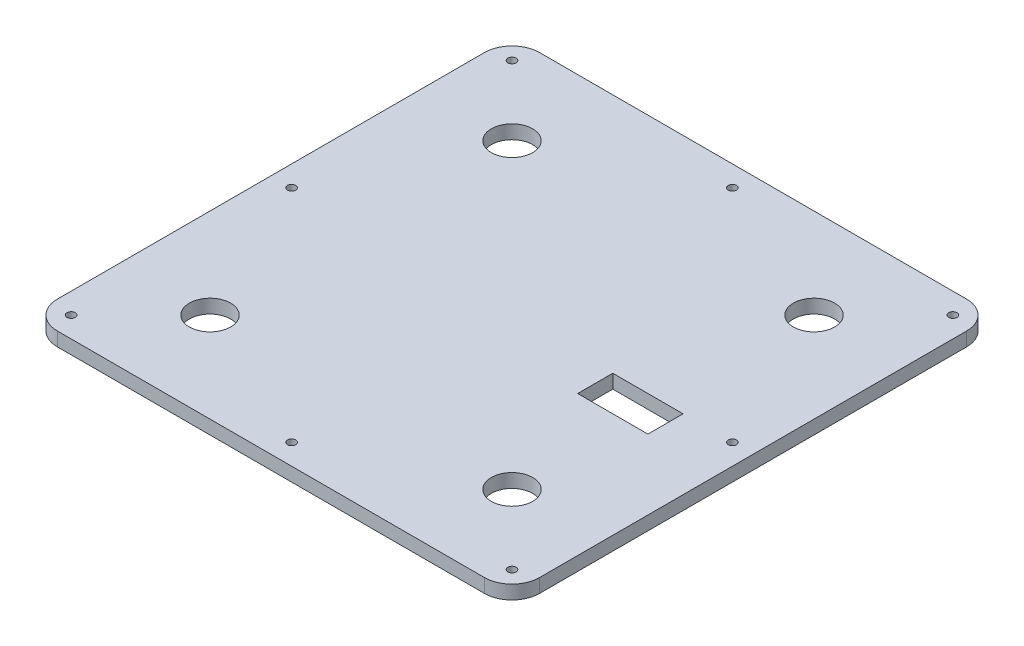
SolidWorks part; units mm, degrees
ref_plane "Front Plane" through (0, 0, 0) normal (0, 0, 1) x (1, 0, 0)
ref_plane "Top Plane" through (0, 0, 0) normal (0, 1, 0) x (1, 0, 0)
ref_plane "Right Plane" through (0, 0, 0) normal (1, 0, 0) x (0, 0, -1)
sketch "Sketch1" plane through (0, 0, 0) normal (0, 1, 0) x (1, 0, 0)
  line L1 (-155, 175) -> (155, 175)
  line L2 (-175, 155) -> (-175, -155)
  line L3 (-155, -175) -> (155, -175)
  line L4 (175, 155) -> (175, -155)
  line L5 (-175, 175) -> (175, -175) construction
  line L6 (-175, -175) -> (175, 175) construction
  circle A0 centre (-109.6016, 109.6016) radius 15
  circle A1 centre (109.6016, 109.6016) radius 15
  circle A2 centre (-109.6016, -109.6016) radius 15
  circle A3 centre (109.6016, -109.6016) radius 15
  arc A4 (-155, 175) -> (-175, 155) centre (-155, 155) ccw
  arc A5 (-175, -155) -> (-155, -175) centre (-155, -155) ccw
  arc A6 (155, -175) -> (175, -155) centre (155, -155) ccw
  arc A7 (155, 175) -> (175, 155) centre (155, 155) cw
  point P0 (0, 0)
  dimension "D3" = 20
  dimension "D4" = 20
  dimension "D7" = 20
  dimension "D8" = 20
  dimension "D1" = 350
  dimension "D2" = 350
  dimension "D5" = 155
  dimension "D6" = 155
extrude "Boss-Extrude1" add sketch "Sketch1" along normal blind 10
sketch "Sketch3" plane through (0, 0, 0) normal (0, -1, 0) x (1, 0, 0)
  line L0 (175, 155) -> (175, -155) construction
  line L1 (155, -175) -> (-155, -175) construction
  line L2 (-155, 175) -> (155, 175) construction
  line L3 (-175, -155) -> (-175, 155) construction
  point P0 (160, 160)
  point P1 (0, 160)
  point P2 (-160, 160)
  point P3 (-160, 0)
  point P4 (-160, -160)
  point P5 (0, -160)
  point P6 (160, -160)
  point P7 (160, 0)
  dimension "D1" = 15
  dimension "D2" = 15
  dimension "D3" = 15
  dimension "D4" = 15
hole_wizard "CSK for M6 Flat Head Machine Screw2" positions "3DSketch2" profile "Sketch5" countersink size "M6" standard "ANSI Metric" end condition through all
sketch3d "3DSketch2"
  point P0 (160, 0, -160)
  point P3 (160, 0, 0)
  point P6 (160, 0, 160)
  point P9 (0, 0, 160)
  point P12 (-160, 0, 160)
  point P15 (-160, 0, 0)
  point P18 (-160, 0, -160)
  point P21 (0, 0, -160)
sketch "Sketch5" plane through (160, 0, -160) normal (1, 0, 0) x (0, 0, -1)
  line L0 (0, 0) -> (0, 10)
  line L1 (0, 10) -> (3, 10)
  line L2 (3, 10) -> (3, 3.3)
  line L3 (3, 3.3) -> (6.3, 0)
  line L5 (6.3, 0) -> (0, 0)
  line L6 (-3, 3.3) -> (-6.3, 0) construction
  line L11 (0, -6.35) -> (0, 107.95) construction
  dimension "Thru Hole Dia." = 6
  dimension "Thru Hole Depth" = 10
  dimension "Near C'Sink Dia." = 12.6
  dimension "Near C'Sink Angle" = 90
sketch "Sketch6" plane through (0, 10, 0) normal (0, 1, 0) x (1, 0, 0)
  line L1 (73.1665, 0) -> (124.1665, 0)
  line L2 (73.1665, 0) -> (73.1665, -25.5)
  line L3 (73.1665, -25.5) -> (124.1665, -25.5)
  line L4 (124.1665, 0) -> (124.1665, -25.5)
  dimension "D1" = 51
  dimension "D2" = 25.5
extrude "Cut-Extrude1" cut sketch "Sketch6" against normal blind 10
